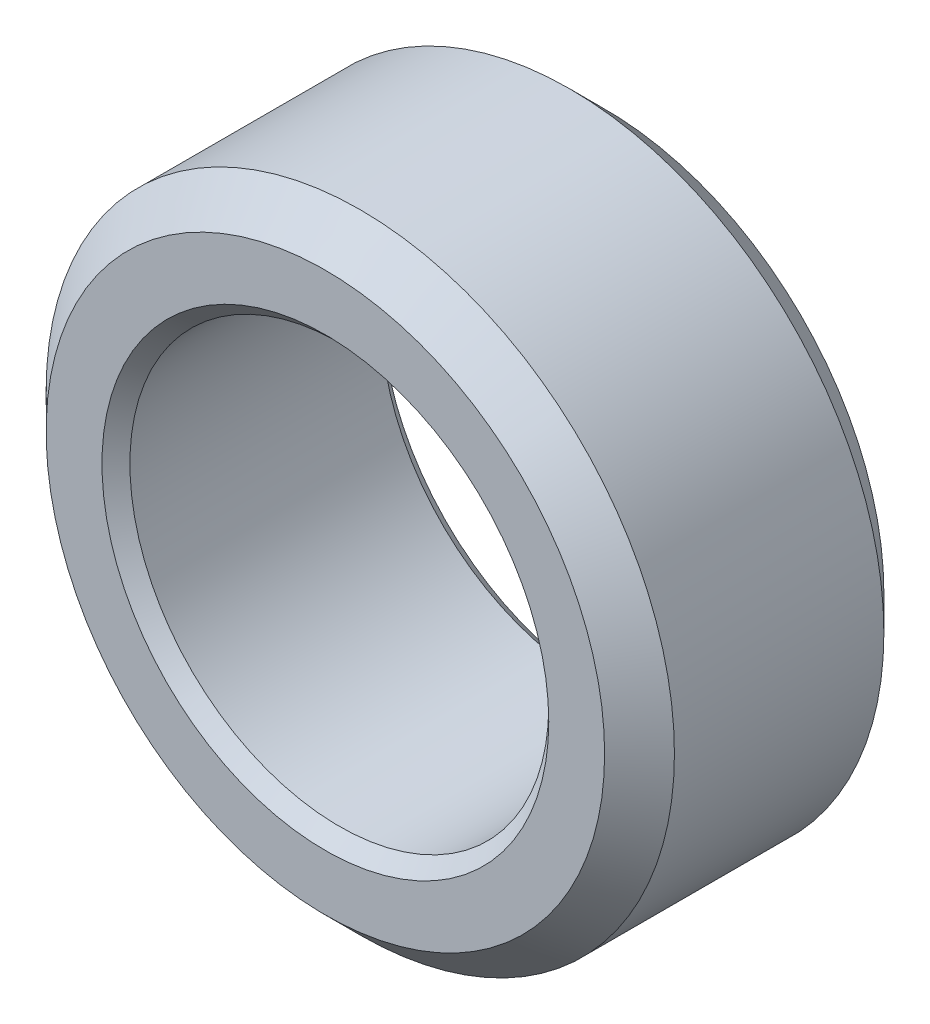
SolidWorks part; units mm, degrees
ref_plane "Plan1" through (0, 0, 0) normal (0, 0, 1) x (1, 0, 0)
ref_plane "Plan2" through (0, 0, 0) normal (0, 1, 0) x (1, 0, 0)
ref_plane "Plan3" through (0, 0, 0) normal (1, 0, 0) x (0, 0, -1)
sketch "Esquisse1" plane through (0, 0, 0) normal (0, 0, 1) x (1, 0, 0)
  circle A0 centre (0, 0) radius 3
  circle A1 centre (0, 0) radius 4.5
  dimension "D1" = 6
  dimension "D2" = 9
extrude "Base-Extrusion" add sketch "Esquisse1" along normal mid plane 4
chamfer "Chanfrein1" distance 0.5 angle 45
chamfer "Chanfrein2" distance 0.2 angle 45
